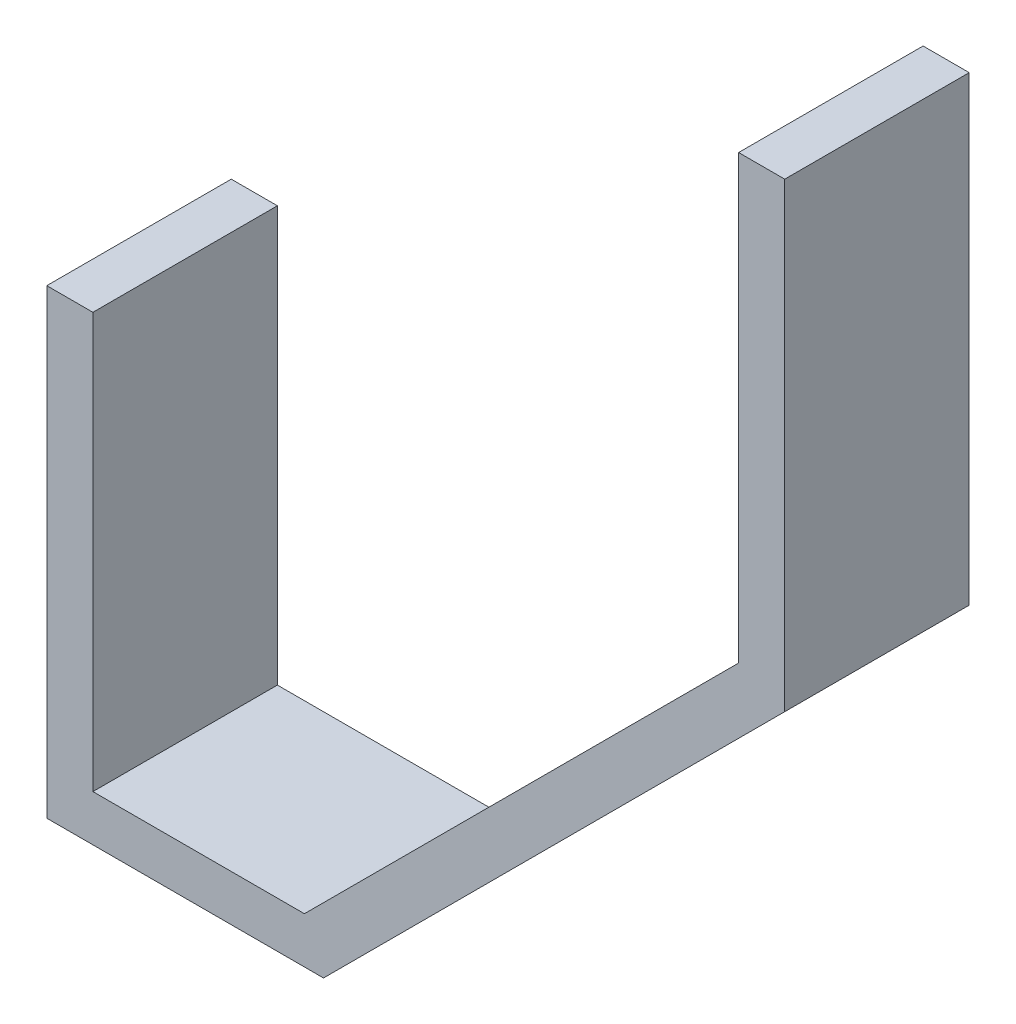
SolidWorks part; units mm, degrees
ref_plane "Спереди" through (0, 0, 0) normal (0, 0, 1) x (1, 0, 0)
ref_plane "Сверху" through (0, 0, 0) normal (0, 1, 0) x (1, 0, 0)
ref_plane "Справа" through (0, 0, 0) normal (1, 0, 0) x (0, 0, -1)
sketch "Эскиз1" plane through (0, 0, 0) normal (0, 0, 1) x (1, 0, 0)
  line L1 (30, 0) -> (80, 50)
  line L2 (80, 50) -> (80, 100)
  line L3 (80, 100) -> (75, 100)
  line L4 (75, 100) -> (75, 52.0711)
  line L5 (75, 52.0711) -> (27.9289, 5)
  line L6 (27.9289, 5) -> (5, 5)
  line L7 (5, 5) -> (5, 50)
  line L8 (5, 50) -> (0, 50)
  line L9 (0, 50) -> (0, 0)
  line L11 (0, 0) -> (30, 0)
  line L12 (5, 5) -> (5, 0) construction
  line L13 (31.4645, 1.4645) -> (27.9289, 5) construction
  dimension "D1" = 5
  dimension "D2" = 50
  dimension "D3" = 80
  dimension "D4" = 100
  dimension "D5" = 45
  dimension "D6" = 30
extrude "Бобышка-Вытянуть1" add sketch "Эскиз1" along normal blind 20
